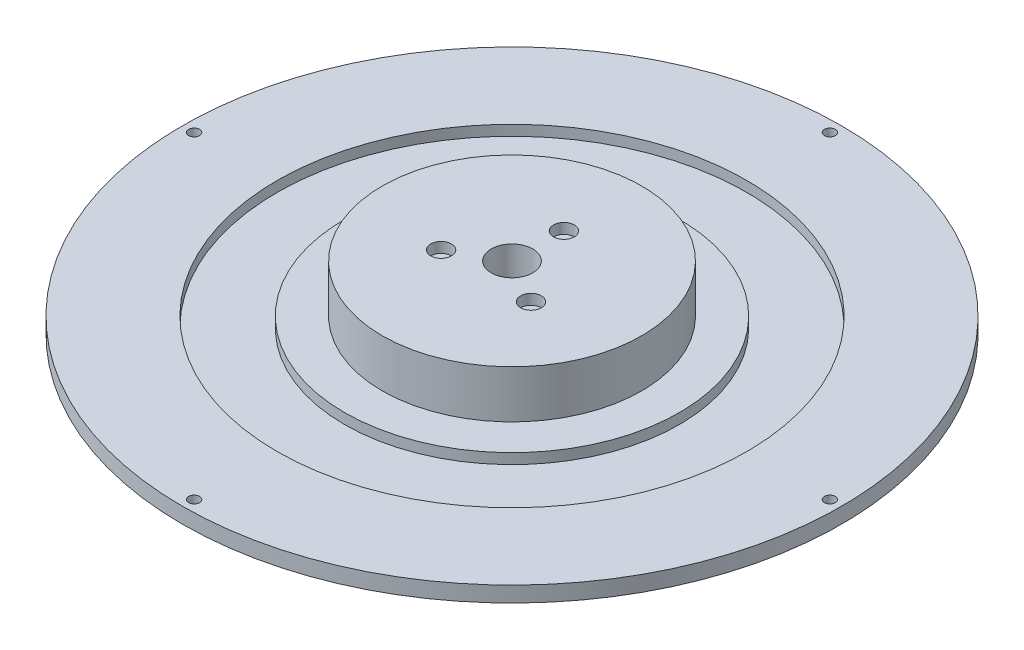
SolidWorks part; units mm, degrees
ref_plane "Front Plane" through (0, 0, 0) normal (0, 0, 1) x (1, 0, 0)
ref_plane "Top Plane" through (0, 0, 0) normal (0, 1, 0) x (1, 0, 0)
ref_plane "Right Plane" through (0, 0, 0) normal (1, 0, 0) x (0, 0, -1)
sketch "Sketch1" plane through (0, 0, 0) normal (0, 1, 0) x (1, 0, 0)
  line L0 (0, 0) -> (0, 61.25) construction
  line L1 (0, 0) -> (61.25, 0) construction
  line L2 (0, 0) -> (0, -61.25) construction
  line L3 (0, 0) -> (-61.25, 0) construction
  circle A0 centre (0, 0) radius 63.5
  circle A1 centre (0, 61.25) radius 1.05
  circle A2 centre (61.25, 0) radius 1.05
  circle A3 centre (0, -61.25) radius 1.05
  circle A4 centre (-61.25, 0) radius 1.05
  point P14 (0, 0)
  dimension "D1" = 127
  dimension "D3" = 2.1
  dimension "D2" = 61.25
  dimension "D4" = 4
extrude "Boss-Extrude1" add sketch "Sketch1" along normal blind 3
sketch "Sketch2" plane through (0, 3, 0) normal (0, 1, 0) x (1, 0, 0)
  circle A0 centre (0, 0) radius 32.25
  circle A1 centre (0, 0) radius 45.25
  dimension "D1" = 90.5
  dimension "D2" = 64.5
extrude "Cut-Extrude1" cut sketch "Sketch2" against normal blind 2
sketch "Sketch4" plane through (0, 3, 0) normal (0, 1, 0) x (1, 0, 0)
  circle A0 centre (0, 0) radius 25
  dimension "D1" = 50
extrude "Boss-Extrude2" add sketch "Sketch4" along normal blind 9.2
sketch "Sketch5" plane through (0, 12.2, 0) normal (0, 1, 0) x (1, 0, 0)
  line L0 (0, 0) -> (0, 10) construction
  line L1 (0, 0) -> (8.6603, -5) construction
  line L2 (0, 0) -> (-8.6603, -5) construction
  circle A0 centre (0, 10) radius 2
  circle A1 centre (8.6603, -5) radius 2
  circle A2 centre (-8.6603, -5) radius 2
  point P11 (0, 0)
  dimension "D2" = 4
  dimension "D1" = 10
  dimension "D3" = 3
extrude "Cut-Extrude2" cut sketch "Sketch5" against normal blind 2
sketch "Sketch6" plane through (0, 12.2, 0) normal (0, 1, 0) x (1, 0, 0)
  circle A0 centre (0, 0) radius 4
  dimension "D1" = 8
extrude "Cut-Extrude3" cut sketch "Sketch6" against normal through all
